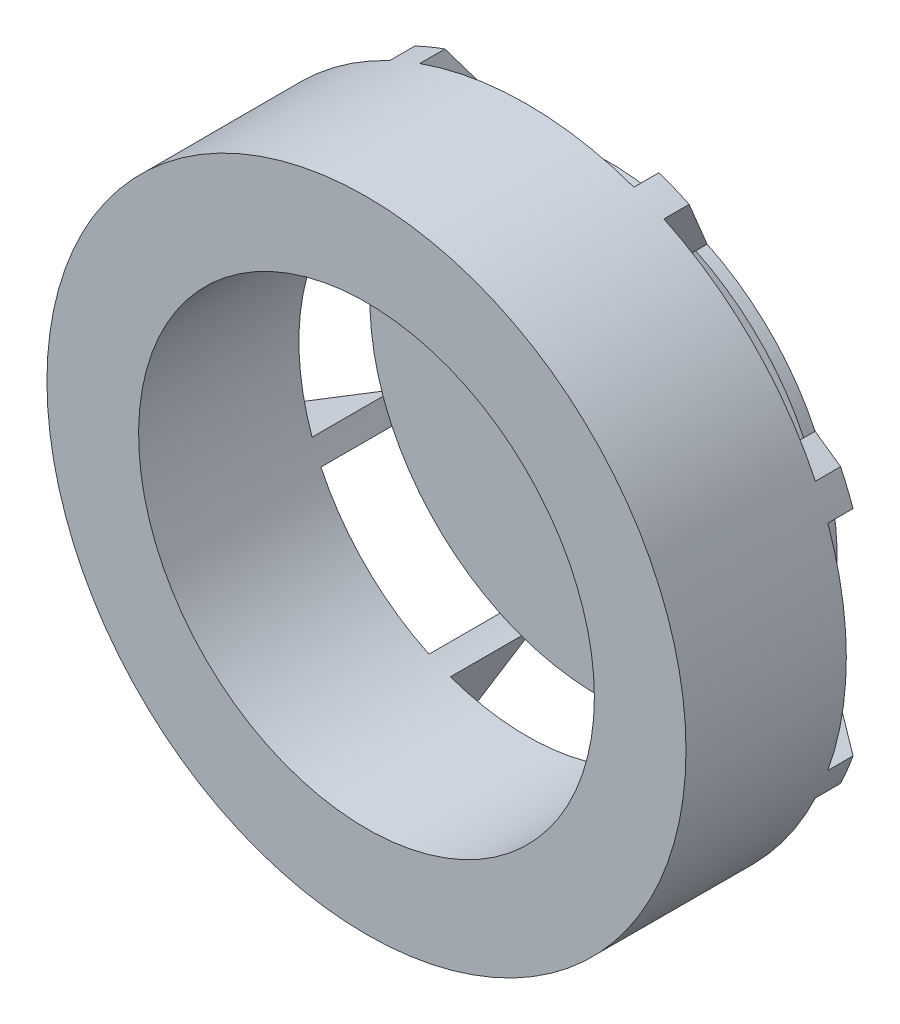
SolidWorks part; units mm, degrees
ref_plane "Ön Düzlem" through (0, 0, 0) normal (0, 0, 1) x (1, 0, 0)
ref_plane "Üst Düzlem" through (0, 0, 0) normal (0, 1, 0) x (1, 0, 0)
ref_plane "Sağ Düzlem" through (0, 0, 0) normal (1, 0, 0) x (0, 0, -1)
sketch "Çizim1" plane through (0, 0, 0) normal (0, 0, 1) x (1, 0, 0)
  circle A0 centre (0, 0) radius 13.95
extrude "Yükseklik-Ekstrüzyon1" add sketch "Çizim1" along normal blind 10.6 contours A0
chamfer "Pah1" distance 4 distance2 2.5 1 edges at (13.95, 0, 0)
sketch "Çizim3" plane through (0, 0, 10.6) normal (0, 0, 1) x (1, 0, 0)
  circle A0 centre (0, 0) radius 2.5
extrude "Kes-Ekstrüzyon1" cut sketch "Çizim3" against normal blind 10.6
sketch "Çizim5" plane through (0, 0, 0) normal (0, 0, -1) x (-1, 0, 0)
  line L1 (-9.3747, 3.3344) -> (-13.1434, 4.6749)
  line L2 (-9.3747, -3.3344) -> (-13.1434, -4.6749)
  circle A0 centre (0, 0) radius 9.95 construction
  circle A1 centre (0, 0) radius 13.95 construction
  arc A2 (-9.3747, 3.3344) -> (-9.3747, -3.3344) centre (0, 0) ccw
  arc A3 (-13.1434, 4.6749) -> (-13.1434, -4.6749) centre (0, 0) ccw
extrude "Kes-Ekstrüzyon2" cut sketch "Çizim5" against normal blind 3.6
pattern_circular "Dairesel Kaplama1" count 8 over 360 about axis through (0, 0, 0) along (0, 0, 1) of "Kes-Ekstrüzyon2"
ref_plane "Düzlem1" through (0, 0, 0.5) normal (0, 0, -1) x (-1, 0, 0)
sketch "Çizim8" plane through (0, 0, 0.5) normal (0, 0, -1) x (-1, 0, 0)
  arc A16 (-9.3747, -3.3344) -> (-8.9867, -4.2711) centre (0, 0) ccw
  arc A17 (-8.9867, -4.2711) -> (-4.2711, -8.9867) centre (0, 0) ccw
  arc A18 (-4.2711, -8.9867) -> (-3.3344, -9.3747) centre (0, 0) ccw
  arc A19 (-3.3344, -9.3747) -> (3.3344, -9.3747) centre (0, 0) ccw
  arc A20 (3.3344, -9.3747) -> (4.2711, -8.9867) centre (0, 0) ccw
  arc A21 (4.2711, -8.9867) -> (8.9867, -4.2711) centre (0, 0) ccw
  arc A22 (8.9867, -4.2711) -> (9.3747, -3.3344) centre (0, 0) ccw
  arc A23 (9.3747, -3.3344) -> (9.3747, 3.3344) centre (0, 0) ccw
  arc A24 (9.3747, 3.3344) -> (8.9867, 4.2711) centre (0, 0) ccw
  arc A25 (8.9867, 4.2711) -> (4.2711, 8.9867) centre (0, 0) ccw
  arc A26 (4.2711, 8.9867) -> (3.3344, 9.3747) centre (0, 0) ccw
  arc A27 (3.3344, 9.3747) -> (-3.3344, 9.3747) centre (0, 0) ccw
  arc A28 (-3.3344, 9.3747) -> (-4.2711, 8.9867) centre (0, 0) ccw
  arc A29 (-4.2711, 8.9867) -> (-8.9867, 4.2711) centre (0, 0) ccw
  arc A30 (-8.9867, 4.2711) -> (-9.3747, 3.3344) centre (0, 0) ccw
  arc A31 (-9.3747, 3.3344) -> (-9.3747, -3.3344) centre (0, 0) ccw
  arc A32 (-9.3747, -3.3344) -> (-8.9867, -4.2711) centre (0, 0) ccw
  arc A33 (-8.9867, -4.2711) -> (-4.2711, -8.9867) centre (0, 0) ccw
  arc A34 (-4.2711, -8.9867) -> (-3.3344, -9.3747) centre (0, 0) ccw
  arc A35 (-3.3344, -9.3747) -> (3.3344, -9.3747) centre (0, 0) ccw
  arc A36 (3.3344, -9.3747) -> (4.2711, -8.9867) centre (0, 0) ccw
  arc A37 (4.2711, -8.9867) -> (8.9867, -4.2711) centre (0, 0) ccw
  arc A38 (8.9867, -4.2711) -> (9.3747, -3.3344) centre (0, 0) ccw
  arc A39 (9.3747, -3.3344) -> (9.3747, 3.3344) centre (0, 0) ccw
  arc A40 (9.3747, 3.3344) -> (8.9867, 4.2711) centre (0, 0) ccw
  arc A41 (8.9867, 4.2711) -> (4.2711, 8.9867) centre (0, 0) ccw
  arc A42 (4.2711, 8.9867) -> (3.3344, 9.3747) centre (0, 0) ccw
  arc A43 (3.3344, 9.3747) -> (-3.3344, 9.3747) centre (0, 0) ccw
  arc A44 (-3.3344, 9.3747) -> (-4.2711, 8.9867) centre (0, 0) ccw
  arc A45 (-4.2711, 8.9867) -> (-8.9867, 4.2711) centre (0, 0) ccw
  arc A46 (-8.9867, 4.2711) -> (-9.3747, 3.3344) centre (0, 0) ccw
  arc A47 (-9.3747, 3.3344) -> (-9.3747, -3.3344) centre (0, 0) ccw
  dimension "D1" = 0
extrude "Kes-Ekstrüzyon3" cut sketch "Çizim8" against normal up to surface (10.1 mm away) up to face at (2.5, 0, 10.6)
